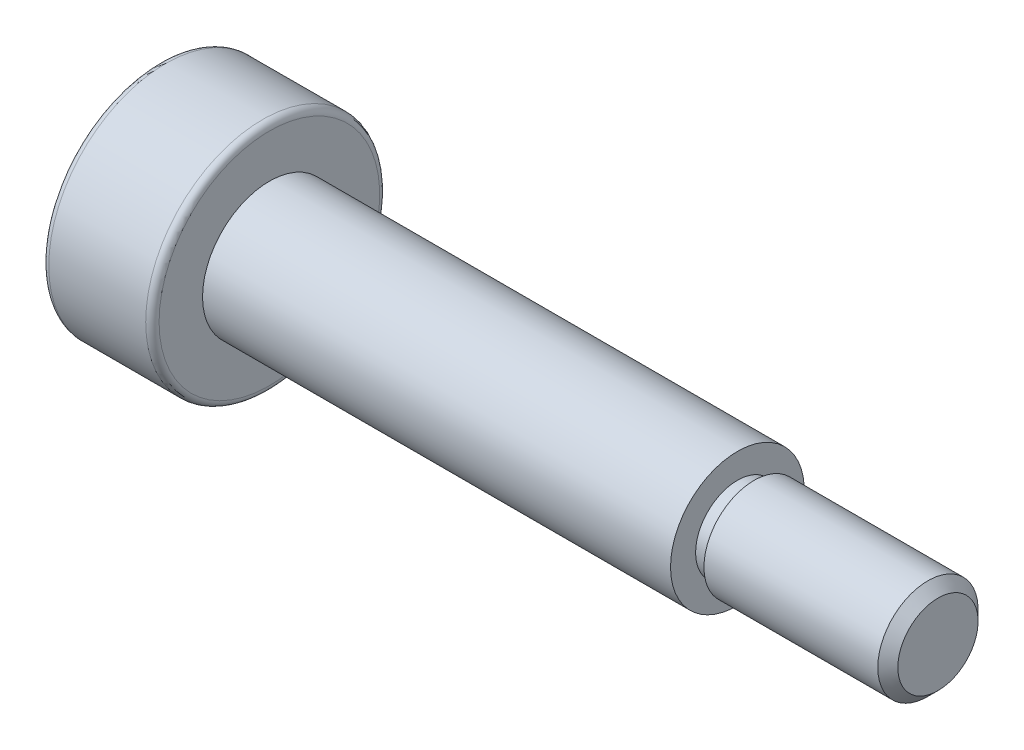
SolidWorks part; units mm, degrees
ref_plane "前视基准面" through (0, 0, 0) normal (0, 0, 1) x (1, 0, 0)
ref_plane "上视基准面" through (0, 0, 0) normal (0, 1, 0) x (1, 0, 0)
ref_plane "右视基准面" through (0, 0, 0) normal (1, 0, 0) x (0, 0, -1)
sketch "草图1" plane through (0, 0, 0) normal (0, 0, 1) x (1, 0, 0)
  line L0 (-11.65, 0) -> (11.65, 0) construction
  line L1 (-11.65, 0) -> (-11.65, 3.5)
  line L2 (-11.65, 3.5) -> (-8.35, 3.5)
  line L3 (-8.35, 3.5) -> (-8.35, 2)
  line L4 (-8.35, 2) -> (5.65, 2)
  line L5 (5.65, 2) -> (5.65, 1.5)
  line L6 (5.65, 1.5) -> (11.65, 1.5)
  line L7 (11.65, 1.5) -> (11.65, 0)
  line L8 (-11.65, 0) -> (11.65, 0)
  dimension "D1" = 4
  dimension "D2" = 7
  dimension "D3" = 3
  dimension "D4" = 6
  dimension "D5" = 14
  dimension "D6" = 3.3
revolve "旋转1" add sketch "草图1" angle 360 about L0
fillet "圆角1" radius 0.2 2 edges at (-8.35, 0, 3.5) (-11.65, 0, 3.5)
chamfer "倒角1" distance 0.3 angle 45 1 edges at (11.65, 0, 1.5)
sketch "草图3" plane through (0, 0, 0) normal (0, 0, 1) x (1, 0, 0)
  line L0 (5.65, 0) -> (11.35, 0) construction
  line L1 (5.65, -1.5) -> (5.65, 1.5) construction
  line L2 (11.35, 1.5) -> (11.35, -1.5) construction
  line L3 (5.65, -2) -> (5.65, 2) construction
  line L4 (5.65, 1.5) -> (6.15, 1.5)
  line L5 (5.65, 1.5) -> (5.65, 1.25)
  line L6 (5.65, 1.25) -> (6.15, 1.25)
  line L7 (6.15, 1.5) -> (6.15, 1.25)
  line L8 (11.35, 1.5) -> (5.65, 1.5) construction
  dimension "D1" = 2.5
  dimension "D2" = 0.5
revolve "切除-旋转1" cut sketch "草图3" angle 360 about L0
sketch "草图4" plane through (-11.65, 0, 0) normal (-1, 0, 0) x (0, 0, 1)
  line L1 (1.7321, 0) -> (0.866, 1.5)
  line L2 (0.866, 1.5) -> (-0.866, 1.5)
  line L3 (-0.866, 1.5) -> (-1.7321, 0)
  line L4 (-1.7321, 0) -> (-0.866, -1.5)
  line L5 (-0.866, -1.5) -> (0.866, -1.5)
  line L6 (0.866, -1.5) -> (1.7321, 0)
  circle A0 centre (0, 0) radius 1.5 construction
  dimension "D1" = 3
extrude "切除-拉伸1" cut sketch "草图4" against normal blind 2
